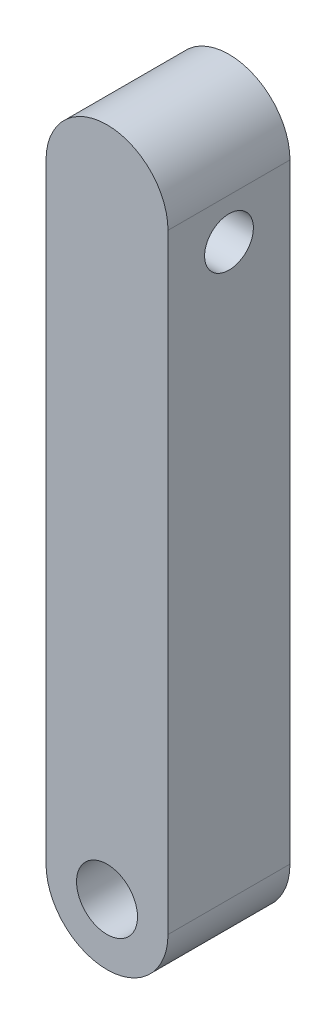
SolidWorks part; units mm, degrees
ref_plane "Front Plane" through (0, 0, 0) normal (0, 0, 1) x (1, 0, 0)
ref_plane "Top Plane" through (0, 0, 0) normal (0, 1, 0) x (1, 0, 0)
ref_plane "Right Plane" through (0, 0, 0) normal (1, 0, 0) x (0, 0, -1)
sketch "Sketch2" plane through (0, 0, 0) normal (0, 0, 1) x (1, 0, 0)
  line L0 (0, -50) -> (0, 50) construction
  line L1 (-10, -50) -> (-10, 50)
  line L2 (10, -50) -> (10, 50)
  arc A0 (-10, -50) -> (10, -50) centre (0, -50) ccw
  arc A1 (10, 50) -> (-10, 50) centre (0, 50) ccw
  circle A3 centre (0, -50) radius 5
  point P2 (0, 0)
  dimension "D1" = 100
  dimension "D2" = 20
extrude "Boss-Extrude1" add sketch "Sketch2" along normal blind 20
sketch "Sketch4" plane through (10, 0, 0) normal (1, 0, 0) x (0, 0, -1)
  circle A0 centre (-10, 43.3554) radius 4
extrude "Cut-Extrude1" cut sketch "Sketch4" against normal blind 26
ref_plane "Plane1" through (0, -50, 0) normal (0, 1, 0) x (1, 0, 0)
sketch "Sketch6" plane through (0, -50, 0) normal (0, 1, 0) x (1, 0, 0)
  line L0 (0, 0) -> (0, -20) construction
  line L2 (-10, -20) -> (10, -20) construction
  line L3 (10, -10) -> (-10, -10) construction
  line L4 (-10, -20) -> (-10, 0) construction
  point P6 (0, 0)
  point P12 (0, -10)
